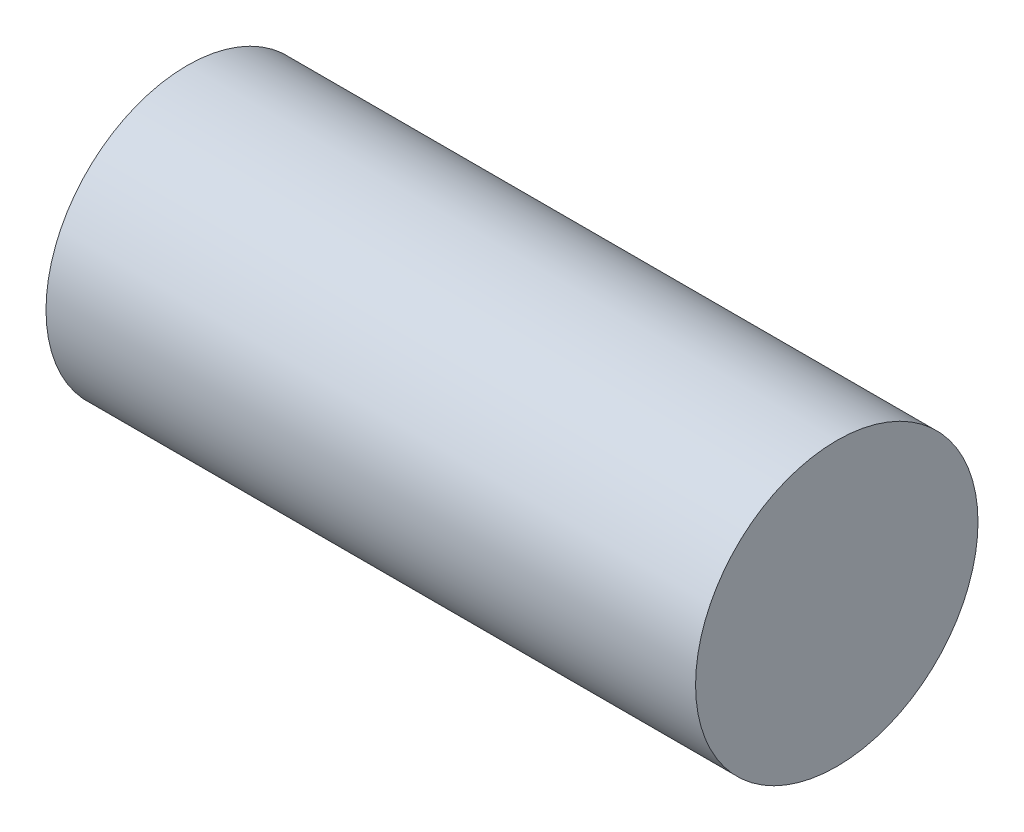
SolidWorks part; units mm, degrees
ref_plane "Front Plane" through (0, 0, 0) normal (0, 0, 1) x (1, 0, 0)
ref_plane "Top Plane" through (0, 0, 0) normal (0, 1, 0) x (1, 0, 0)
ref_plane "Right Plane" through (0, 0, 0) normal (1, 0, 0) x (0, 0, -1)
sketch "Sketch1" plane through (0, 0, 0) normal (0, 0, 1) x (1, 0, 0)
  line L0 (-30.1057, 0) -> (30.1057, 0) construction
  line L1 (-23, 10) -> (23, 10)
  line L2 (23, 10) -> (23, 0)
  line L3 (-23, 10) -> (-23, 0)
  line L4 (0, 10) -> (0, 0) construction
  line L5 (-23, 0) -> (23, 0)
  point P3 (0, 0)
  dimension "D1" = 46
  dimension "D2" = 20
revolve "Revolve1" add sketch "Sketch1" angle 360 about L0
